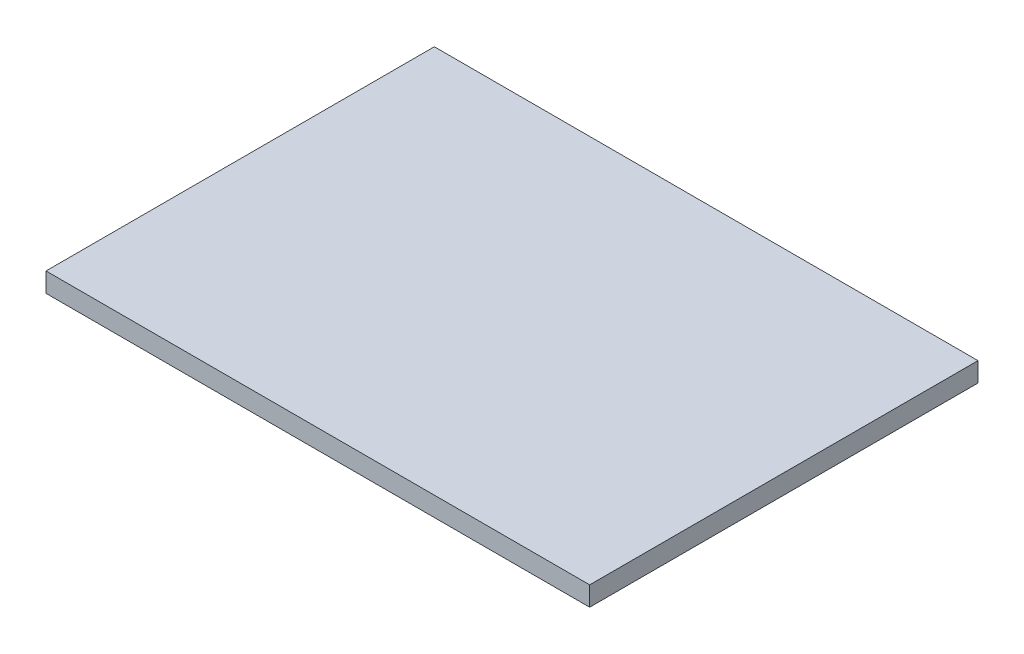
SolidWorks part; units mm, degrees
material "Alloy Steel (SS)"
ref_plane "Front Plane" through (0, 0, 0) normal (0, 0, 1) x (1, 0, 0)
ref_plane "Top Plane" through (0, 0, 0) normal (0, 1, 0) x (1, 0, 0)
ref_plane "Right Plane" through (0, 0, 0) normal (1, 0, 0) x (0, 0, -1)
sketch "Sketch1" plane through (0, 0, 0) normal (0, 1, 0) x (1, 0, 0)
  line L1 (-175.7216, 120.2519) -> (535.4784, 120.2519)
  line L2 (-175.7216, 120.2519) -> (-175.7216, -387.7481)
  line L3 (-175.7216, -387.7481) -> (535.4784, -387.7481)
  line L4 (535.4784, 120.2519) -> (535.4784, -387.7481)
  dimension "D1" = 711.2
  dimension "D2" = 508
extrude "Boss-Extrude1" add sketch "Sketch1" along normal blind 25.4
